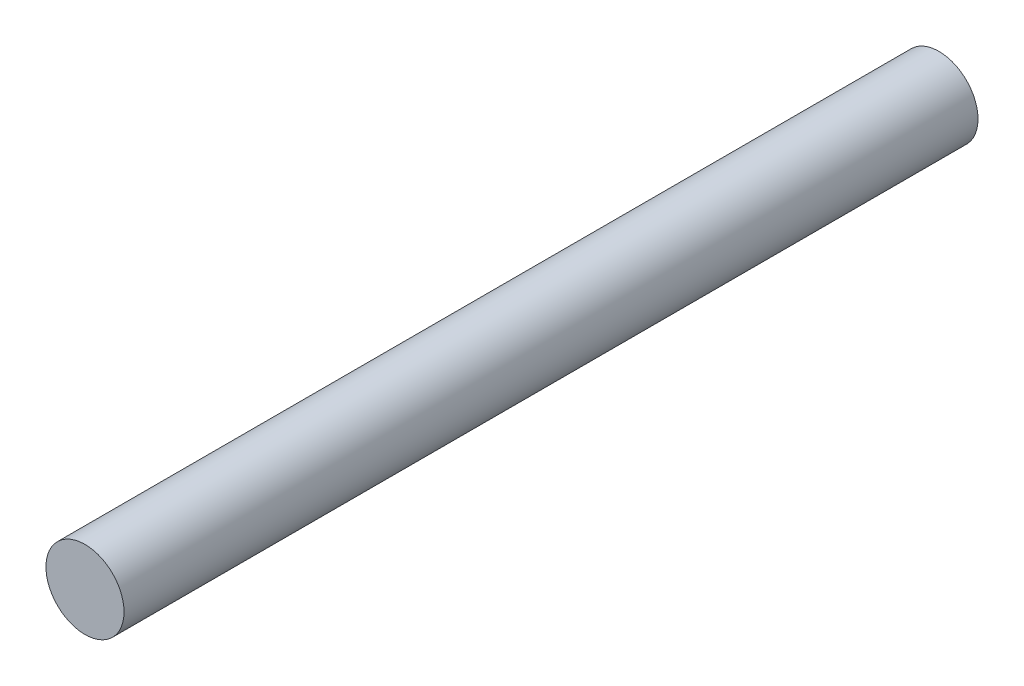
SolidWorks part; units mm, degrees
ref_plane "Alzado" through (0, 0, 0) normal (0, 0, 1) x (1, 0, 0)
ref_plane "Planta" through (0, 0, 0) normal (0, 1, 0) x (1, 0, 0)
ref_plane "Vista lateral" through (0, 0, 0) normal (1, 0, 0) x (0, 0, -1)
sketch "Croquis1" plane through (0, 0, 0) normal (0, 0, 1) x (1, 0, 0)
  circle A0 centre (0, 0) radius 1.5
  dimension "D1" = 3
extrude "Saliente-Extruir1" add sketch "Croquis1" against normal blind 32.8
